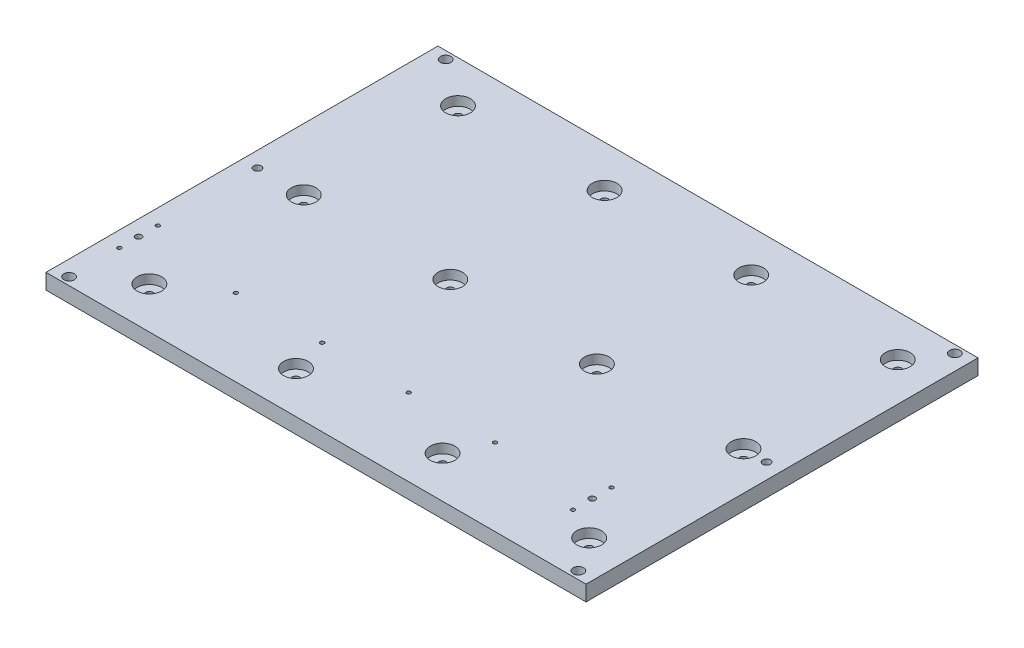
SolidWorks part; units mm, degrees
ref_plane "Front Plane" through (0, 0, 0) normal (0, 0, 1) x (1, 0, 0)
ref_plane "Top Plane" through (0, 0, 0) normal (0, 1, 0) x (1, 0, 0)
ref_plane "Right Plane" through (0, 0, 0) normal (1, 0, 0) x (0, 0, -1)
sketch "Sketch2" plane through (0, 0, 0) normal (0, 1, 0) x (1, 0, 0)
  line L5 (0, 0) -> (920, 0)
  line L6 (0, 0) -> (0, 264)
  line L7 (0, 264) -> (920, 264)
  line L8 (920, 0) -> (920, 264)
  dimension "D1" = 264
  dimension "D2" = 920
extrude "Boss-Extrude1" add sketch "Sketch2" along normal blind 10
sketch "Sketch1" plane through (0, 10, 0) normal (0, 1, 0) x (1, 0, 0)
  line L0 (0, 132) -> (920, 132) construction
  line L1 (0, 0) -> (920, 0) construction
  line L2 (0, 0) -> (0, 264) construction
  line L3 (0, 264) -> (920, 264) construction
  line L4 (920, 0) -> (920, 264) construction
  line L5 (40, 264) -> (40, 0) construction
  line L6 (0, 182) -> (920, 182) construction
  line L7 (0, 182) -> (0, 82) construction
  line L8 (0, 82) -> (920, 82) construction
  line L9 (920, 182) -> (920, 82) construction
  line L10 (0, 232) -> (920, 232) construction
  line L11 (0, 232) -> (0, 32) construction
  line L12 (0, 32) -> (920, 32) construction
  line L13 (920, 232) -> (920, 32) construction
  line L14 (0, 157) -> (920, 157) construction
  line L15 (0, 157) -> (0, 107) construction
  line L16 (0, 107) -> (920, 107) construction
  line L17 (920, 157) -> (920, 107) construction
  line L18 (0, 157) -> (920, 157) construction
  line L19 (0, 157) -> (0, 207) construction
  line L20 (0, 207) -> (920, 207) construction
  line L21 (920, 157) -> (920, 207) construction
  line L22 (920, 207) -> (0, 207) construction
  line L23 (920, 207) -> (920, 257) construction
  line L24 (920, 257) -> (0, 257) construction
  line L25 (0, 207) -> (0, 257) construction
  line L26 (0, 107) -> (920, 107) construction
  line L27 (0, 107) -> (0, 57) construction
  line L28 (0, 57) -> (920, 57) construction
  line L29 (920, 107) -> (920, 57) construction
  line L30 (920, 57) -> (0, 57) construction
  line L31 (920, 57) -> (920, 7) construction
  line L32 (920, 7) -> (0, 7) construction
  line L33 (0, 57) -> (0, 7) construction
  circle A0 centre (40, 32) radius 2.5
  circle A1 centre (135, 32) radius 2.5
  circle A2 centre (230, 32) radius 2.5
  circle A3 centre (325, 32) radius 2.5
  circle A4 centre (420, 32) radius 2.5
  circle A5 centre (515, 32) radius 2.5
  circle A6 centre (610, 32) radius 2.5
  circle A7 centre (705, 32) radius 2.5
  circle A8 centre (800, 32) radius 2.5
  circle A9 centre (895, 32) radius 2.5
  circle A10 centre (135, 132) radius 2.5
  circle A11 centre (230, 132) radius 2.5
  circle A12 centre (325, 132) radius 2.5
  circle A13 centre (420, 132) radius 2.5
  circle A14 centre (515, 132) radius 2.5
  circle A15 centre (610, 132) radius 2.5
  circle A16 centre (705, 132) radius 2.5
  circle A17 centre (800, 132) radius 2.5
  circle A18 centre (895, 132) radius 2.5
  circle A19 centre (135, 232) radius 2.5
  circle A20 centre (230, 232) radius 2.5
  circle A21 centre (325, 232) radius 2.5
  circle A22 centre (420, 232) radius 2.5
  circle A23 centre (515, 232) radius 2.5
  circle A24 centre (610, 232) radius 2.5
  circle A25 centre (705, 232) radius 2.5
  circle A26 centre (800, 232) radius 2.5
  circle A27 centre (895, 232) radius 2.5
  circle A28 centre (40, 132) radius 2.5
  circle A29 centre (40, 232) radius 2.5
  dimension "D14" = 5
  dimension "D1" = 264
  dimension "D2" = 920
  dimension "D3" = 50
  dimension "D4" = 50
  dimension "D5" = 50
  dimension "D6" = 50
  dimension "D7" = 50
  dimension "D8" = 50
  dimension "D9" = 50
  dimension "D10" = 50
  dimension "D11" = 50
  dimension "D12" = 25
  dimension "D13" = 40
  dimension "D15" = 10
  dimension "D16" = 3
extrude "Cut-Extrude2" cut sketch "Sketch1" against normal blind 18
sketch "Sketch3" plane through (0, 10, 0) normal (0, 1, 0) x (1, 0, 0)
  circle A0 centre (40, 32) radius 8
  circle A1 centre (135, 32) radius 8
  circle A2 centre (230, 32) radius 8
  circle A3 centre (325, 32) radius 8
  circle A4 centre (420, 32) radius 8
  circle A5 centre (515, 32) radius 8
  circle A6 centre (610, 32) radius 8
  circle A7 centre (705, 32) radius 8
  circle A8 centre (800, 32) radius 8
  circle A9 centre (895, 32) radius 8
  circle A10 centre (135, 132) radius 8
  circle A11 centre (230, 132) radius 8
  circle A12 centre (325, 132) radius 8
  circle A13 centre (420, 132) radius 8
  circle A14 centre (515, 132) radius 8
  circle A15 centre (610, 132) radius 8
  circle A16 centre (705, 132) radius 8
  circle A17 centre (800, 132) radius 8
  circle A18 centre (895, 132) radius 8
  circle A19 centre (135, 232) radius 8
  circle A20 centre (230, 232) radius 8
  circle A21 centre (325, 232) radius 8
  circle A22 centre (420, 232) radius 8
  circle A23 centre (515, 232) radius 8
  circle A24 centre (610, 232) radius 8
  circle A25 centre (705, 232) radius 8
  circle A26 centre (800, 232) radius 8
  circle A27 centre (895, 232) radius 8
  circle A28 centre (40, 132) radius 8
  circle A29 centre (40, 232) radius 8
  dimension "D1" = 16
  dimension "D2" = 10
  dimension "D3" = 3
extrude "Cut-Extrude3" cut sketch "Sketch3" against normal blind 6
sketch "Sketch4" plane through (0, 10, 0) normal (0, 1, 0) x (1, 0, 0)
  line L0 (0, 0) -> (920, 0) construction
  line L1 (920, 264) -> (350, 264)
  line L2 (920, 264) -> (920, 0)
  line L3 (920, 0) -> (350, 0)
  line L4 (350, 264) -> (350, 0)
  line L5 (0, 264) -> (0, 0) construction
  dimension "D1" = 350
extrude "Cut-Extrude4" cut sketch "Sketch4" against normal blind 20
sketch "Sketch5" plane through (0, 10, 0) normal (0, 1, 0) x (1, 0, 0)
  line L0 (175, 264) -> (175, 0) construction
  line L1 (175, 132) -> (350, 132) construction
  line L2 (175, 132) -> (0, 132) construction
  line L4 (0, 0) -> (350, 0)
  line L5 (350, 0) -> (350, 264)
  line L6 (350, 264) -> (0, 264)
  line L7 (0, 264) -> (0, 0)
  line L8 (0, 0) -> (350, 0)
  line L9 (350, 0) -> (350, 264)
  line L10 (350, 264) -> (0, 264)
  line L11 (0, 264) -> (0, 0)
  dimension "D3" = 350
  dimension "D4" = 264
  dimension "D1" = 0
sketch "Sketch6" plane through (0, 10, 0) normal (0, 1, 0) x (1, 0, 0)
  line L0 (40, 132) -> (0, 132) construction
  line L1 (0, 264) -> (0, 0) construction
  line L2 (20, 264) -> (20, 0) construction
  line L3 (350, 264) -> (0, 264) construction
  line L4 (0, 0) -> (350, 0) construction
  line L5 (40, 132) -> (20, 132) construction
  dimension "D1" = 20
sketch "Sketch7" plane through (0, 10, 0) normal (0, 1, 0) x (1, 0, 0)
  line L0 (350, 264) -> (0, 264) construction
  line L1 (10, 254) -> (340, 254) construction
  line L2 (10, 254) -> (10, 10) construction
  line L3 (10, 10) -> (340, 10) construction
  line L4 (340, 254) -> (340, 10) construction
  line L5 (350, 0) -> (350, 264) construction
  line L6 (175, 254) -> (175, 264) construction
  line L7 (10, 132) -> (0, 132) construction
  line L9 (175, 132) -> (0, 132) construction
  line L10 (175, 132) -> (0, 132) construction
  line L12 (20, 7.6) -> (20, 256.4) construction
  line L13 (175, 132) -> (340, 132) construction
  line L15 (175, 254) -> (175, 132) construction
  line L16 (175, 132) -> (175, 10) construction
  line L17 (175, 10) -> (175, 0) construction
  line L18 (0, 0) -> (350, 0) construction
  line L19 (340, 132) -> (350, 132) construction
  circle A1 centre (10, 254) radius 3.4
  circle A2 centre (340, 254) radius 3.4
  circle A3 centre (340, 10) radius 3.4
  circle A4 centre (10, 10) radius 3.4
  circle A6 centre (20, 132) radius 4 construction
  circle A8 centre (10, 132) radius 2.5
  circle A10 centre (340, 132) radius 2.5
  dimension "D1" = 10
  dimension "D3" = 6.8
  dimension "D5" = 5
  dimension "D6" = 8
  dimension "D7" = 6.8
  dimension "D2" = 10
  dimension "D4" = 10
extrude "Cut-Extrude5" cut sketch "Sketch7" against normal blind 20
sketch "Sketch8" plane through (0, 10, 0) normal (0, 1, 0) x (1, 0, 0)
  line L0 (350, 0) -> (350, 264) construction
  line L1 (0, 264) -> (350, 264)
  line L2 (0, 264) -> (0, 259)
  line L3 (0, 259) -> (350, 259)
  line L4 (350, 264) -> (350, 259)
  line L6 (0, 0) -> (350, 0)
  line L7 (0, 0) -> (0, 5)
  line L8 (0, 5) -> (350, 5)
  line L9 (350, 0) -> (350, 5)
  dimension "D1" = 5
extrude "Cut-Extrude6" cut sketch "Sketch8" against normal blind 10
sketch "Sketch9" plane through (0, 10, 0) normal (0, 1, 0) x (1, 0, 0)
  line L0 (10, 67.5) -> (10, 42.5) construction
  line L1 (10, 55) -> (0, 55) construction
  line L2 (0, 259) -> (0, 5) construction
  line L3 (350, 5) -> (0, 5) construction
  line L4 (157, 259) -> (157, 5) construction
  line L5 (0, 264) -> (0, 0) construction
  line L6 (0, 259) -> (350, 259) construction
  line L7 (10, 55) -> (157, 55) construction
  circle A0 centre (10, 67.5) radius 1.25
  circle A1 centre (10, 42.5) radius 1.25
  circle A2 centre (304, 67.5) radius 1.25
  circle A3 centre (304, 42.5) radius 1.25
  circle A4 centre (73, 55) radius 1.25
  circle A5 centre (129, 55) radius 1.25
  circle A6 centre (185, 55) radius 1.25
  circle A7 centre (241, 55) radius 1.25
  circle A8 centre (10, 55) radius 2
  circle A9 centre (304, 55) radius 2
  dimension "D4" = 2.5
  dimension "D5" = 157
  dimension "D6" = 56
  dimension "D7" = 28
  dimension "D8" = 4
  dimension "D1" = 50
  dimension "D2" = 10
  dimension "D3" = 25
extrude "Cut-Extrude7" cut sketch "Sketch9" against normal blind 10
